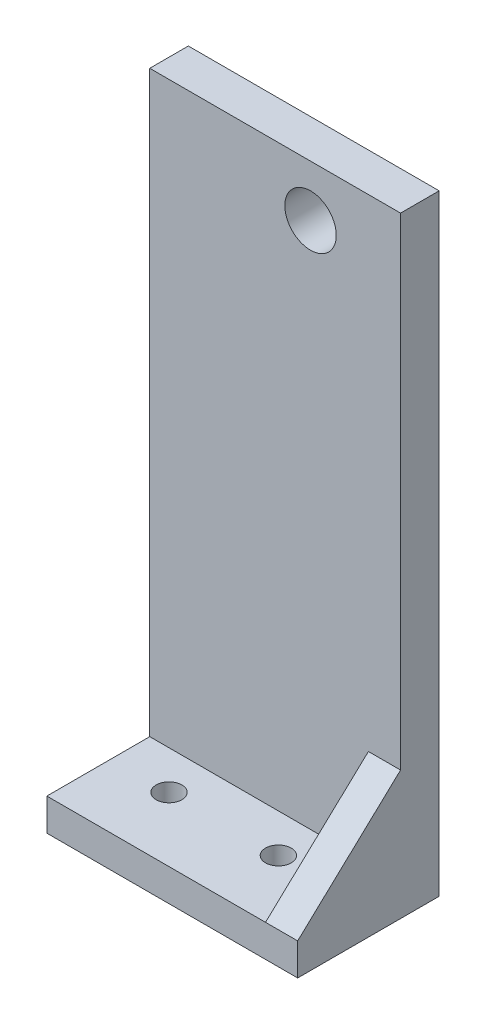
SolidWorks part; units mm, degrees
ref_plane "Front Plane" through (0, 0, 0) normal (0, 0, 1) x (1, 0, 0)
ref_plane "Top Plane" through (0, 0, 0) normal (0, 1, 0) x (1, 0, 0)
ref_plane "Right Plane" through (0, 0, 0) normal (1, 0, 0) x (0, 0, -1)
sketch "Sketch1" plane through (0, 0, 0) normal (0, 1, 0) x (1, 0, 0)
  line L0 (-9, 12) -> (30, 12)
  line L1 (30, 12) -> (30, -10)
  line L2 (30, -10) -> (-9, -10)
  line L3 (-9, -10) -> (-9, 12)
  line L4 (0, 0) -> (17, 0) construction
  circle A0 centre (0, 0) radius 2
  circle A1 centre (17, 0) radius 2
  dimension "D2" = 4
  dimension "D3" = 4
  dimension "D1" = 17
  dimension "D4" = 12
  dimension "D5" = 22
  dimension "D6" = 22
  dimension "D7" = 13
  dimension "D8" = 9
extrude "Boss-Extrude1" add sketch "Sketch1" along normal blind 5
sketch "Sketch4" plane through (0, 0, -12) normal (0, 0, -1) x (-1, 0, 0)
  line L0 (-30, 5) -> (9, 5)
  line L1 (9, 5) -> (9, 15)
  line L3 (-30, 15) -> (-30, 5)
  line L7 (-15, 5) -> (-19, 5) construction
  line L8 (-15, 5) -> (-19, 5)
  line L9 (-16, 87) -> (-16, 15) construction
  line L10 (-16, 15) -> (9, 15) construction
  line L11 (-30, 15) -> (-30, 95)
  line L12 (-30, 95) -> (9, 95)
  line L13 (9, 15) -> (9, 95)
  line L14 (-16, 15) -> (-30, 15) construction
  circle A0 centre (-16, 87) radius 4
  dimension "D6" = 8
  dimension "D1" = 10
  dimension "D2" = 14
  dimension "D3" = 72
  dimension "D4" = 80
extrude "Boss-Extrude2" add sketch "Sketch4" against normal blind 6
sketch "Sketch5" plane through (30, 0, 0) normal (1, 0, 0) x (0, 0, -1)
  line L0 (-10, 5) -> (6, 5)
  line L1 (6, 5) -> (6, 20)
  line L2 (6, 5) -> (6, 95) construction
  line L3 (6, 20) -> (-10, 5)
  dimension "D1" = 15
extrude "Boss-Extrude3" add sketch "Sketch5" against normal blind 5
